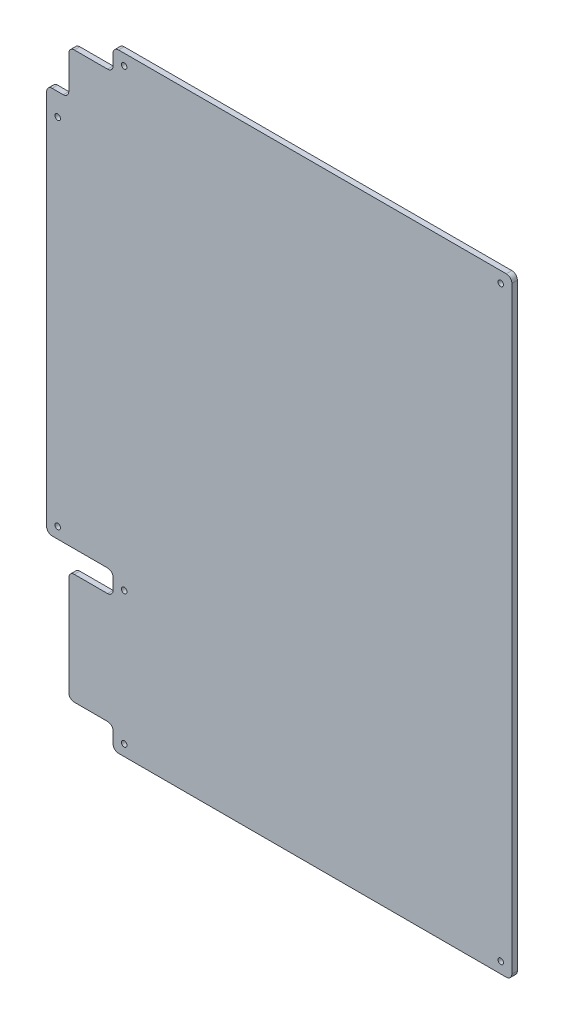
SolidWorks part; units mm, degrees
material "丙烯酸(中高冲击)"
ref_plane "前视基准面" through (0, 0, 0) normal (0, 0, 1) x (1, 0, 0)
ref_plane "上视基准面" through (0, 0, 0) normal (0, 1, 0) x (1, 0, 0)
ref_plane "右视基准面" through (0, 0, 0) normal (1, 0, 0) x (0, 0, -1)
sketch "草图1" plane through (0, 0, 0) normal (0, 0, 1) x (1, 0, 0)
  line L1 (-210, 275) -> (210, 275)
  line L2 (-210, 275) -> (-210, -275)
  line L3 (-210, -275) -> (210, -275)
  line L4 (210, 275) -> (210, -275)
  line L5 (-210, 275) -> (210, -275) construction
  line L6 (-210, -275) -> (210, 275) construction
  point P0 (0, 0)
  dimension "D1" = 420
  dimension "D2" = 550
extrude "凸台-拉伸1" add sketch "草图1" along normal blind 5
sketch "草图2" plane through (0, 0, 5) normal (0, 0, 1) x (1, 0, 0)
  line L1 (-190, 255) -> (-190, 215)
  line L2 (-190, -255) -> (-150, -255)
  line L4 (210, -275) -> (210, 275)
  line L5 (210, 275) -> (-210, 275)
  line L6 (-210, 275) -> (-210, -275)
  line L7 (-210, -275) -> (210, -275)
  line L10 (-210, 275) -> (-210, 215)
  line L11 (-210, -275) -> (-150, -275)
  line L12 (-150, 275) -> (-150, 255)
  line L16 (-150, 275) -> (-210, 275)
  line L17 (210, 275) -> (-210, 275) construction
  line L18 (-150, 255) -> (-190, 255)
  line L19 (190, 255) -> (-190, 255) construction
  line L20 (-190, 215) -> (-210, 215)
  line L23 (-190, -255) -> (190, -255) construction
  line L25 (-210, -275) -> (210, -275) construction
  line L27 (210, -275) -> (210, 275) construction
  line L29 (190, -255) -> (190, 255) construction
  line L31 (-150, -255) -> (-150, -275)
  line L32 (-190, -155) -> (-190, -255)
  line L33 (-190, 255) -> (-190, -255) construction
  line L35 (-210, 275) -> (-210, -275) construction
  line L36 (210, 275) -> (-210, 275) construction
  line L37 (-210, 275) -> (-210, -275) construction
  line L38 (2.75, 0) -> (-2.75, 0) construction
  line L41 (-210, -135) -> (-150, -135)
  line L42 (-150, -135) -> (-150, -155)
  line L43 (-150, -155) -> (-190, -155)
  line L44 (-210, -135) -> (-210, -275)
  line L45 (210, 275) -> (-210, 275) construction
  line L46 (210, -275) -> (210, 275) construction
  line L47 (-210, -275) -> (210, -275) construction
  circle A0 centre (-200, 195) radius 2.5
  circle A1 centre (-140, 265) radius 2.5
  circle A3 centre (-140, -265) radius 2.5
  circle A8 centre (-140, -145) radius 2.5
  circle A9 centre (-200, -125) radius 2.5
  circle A10 centre (200, 265) radius 2.5
  circle A11 centre (200, -265) radius 2.5
  dimension "D8" = 5
  dimension "D9" = 10
  dimension "D10" = 10
  dimension "D11" = 5
  dimension "D12" = 10
  dimension "D13" = 5
  dimension "D14" = 10
  dimension "D15" = 10
  dimension "D18" = 5
  dimension "D19" = 10
  dimension "D20" = 60
  dimension "D21" = 10
  dimension "D22" = 5
  dimension "D23" = 10
  dimension "D24" = 10
  dimension "D3" = 5
  dimension "D4" = 10
  dimension "D6" = 10
  dimension "D5" = 60
  dimension "D7" = 20
  dimension "D16" = 140
  dimension "D17" = 20
  dimension "D1" = 0
  dimension "D2" = 20
extrude "切除-拉伸1" cut sketch "草图2" against normal blind 15
fillet "圆角1" radius 5 14 edges at (-150, -275, 2.5) (-150, -255, 2.5) (-190, -255, 2.5) (-190, -155, 2.5) (-150, -155, 2.5) (-150, -135, 2.5) (-210, -135, 2.5) (-210, 215, 2.5) (-190, 215, 2.5) (-190, 255, 2.5) (-150, 255, 2.5) (-150, 275, 2.5) (210, -275, 2.5) (210, 275, 2.5)
